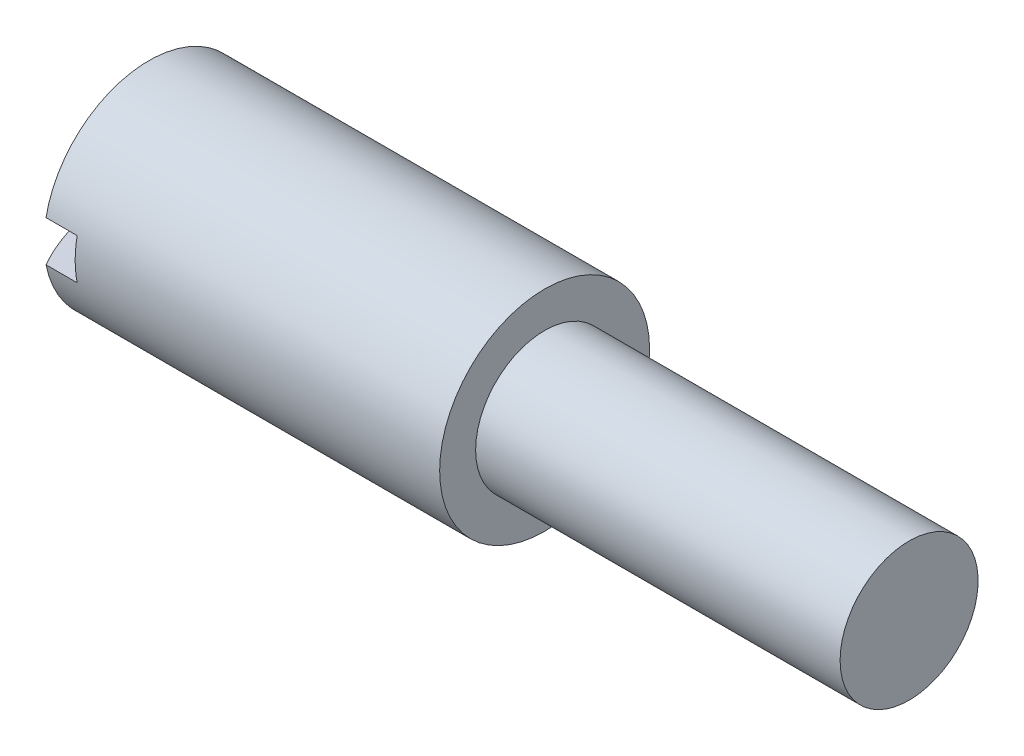
SolidWorks part; units mm, degrees
revolve "BaseBody" add sketch "BodySke" angle 360 about L5
sketch "BodySke" plane through (0, 0, 0) normal (0, 0, 1) x (1, 0, 0)
  line L0 (0.735, -2.7432) -> (47.1574, -2.7432) construction
  line L1 (14.351, 0) -> (14.351, 1.4605)
  line L2 (0.735, 2.7432) -> (13.0683, 2.7432)
  line L3 (14.351, 1.4605) -> (13.0683, 2.7432)
  line L4 (14.351, 0) -> (0, 0)
  line L5 (-12.7, 0) -> (88.9, 0) construction
  line L6 (14.351, 1.4605) -> (14.351, 19.05) construction
  line L7 (14.351, -1.4605) -> (13.0683, -2.7432) construction
  line L8 (1.0592, 12.7) -> (1.0592, -3.175) construction
  arc A1 (0.735, 2.7432) -> (0, 0) centre (5.4864, 0) ccw
  dimension "Crown_radius" = 5.4864
  dimension "Diameter" = 5.4864
  dimension "Nose_ch_ang" = 45
  dimension "Length" = 14.351
  dimension "Flat_dia" = 2.921
  dimension "Advance" = 1.0592
cosmetic thread "ThreadCosmetic" [suppressed] parameters "Thread_minor"=4.2266
extrude "Slot" cut sketch "Sketch2" along normal blind 1.5494
sketch "Sketch2" plane through (0, 0, 0) normal (1, 0, 0) x (0, 0, -1)
  line L1 (2.7432, -0.5334) -> (-2.7432, -0.5334)
  line L2 (2.7432, -0.5334) -> (2.7432, 0.5334)
  line L3 (2.7432, 0.5334) -> (-2.7432, 0.5334)
  line L4 (-2.7432, -0.5334) -> (-2.7432, 0.5334)
  dimension "D1" = 5.4864
  dimension "Slot_width" = 1.0668
  dimension "D3" = 2.7432
  dimension "D2" = 0.5334
material "AISI 1020"
ref_plane "Plane1" through (0, 0, 0) normal (0, 0, 1) x (1, 0, 0)
ref_plane "Plane2" through (0, 0, 0) normal (0, 1, 0) x (1, 0, 0)
ref_plane "Plane3" through (0, 0, 0) normal (1, 0, 0) x (0, 0, -1)
other "Configuration Table"
sketch "ThdSchSke" plane through (0, 0, 0) normal (0, 0, 1) x (1, 0, 0)
  line L0 (0.735, -2.1133) -> (0.294, -2.7432)
  line L1 (0.735, -2.1133) -> (1.1761, -2.7432)
  line L2 (1.1761, -2.7432) -> (1.1761, -3.429)
  line L3 (-3.175, 0) -> (5.1513, 0) construction
  line L4 (0.735, -2.7432) -> (0.735, -0.5334) construction
  line L5 (1.1761, -3.429) -> (0.294, -3.429)
  line L6 (0.294, -3.429) -> (0.294, -2.7432)
  dimension "Diameter" = 5.4864
  dimension "Thread_minor" = 4.2266
revolve "ThreadSchematic" [suppressed] cut sketch "ThdSchSke" angle 360 about L3
pattern_linear "ThdSchPat" [suppressed]
ref_plane "Plano1" through (11.0744, 0, 0) normal (-1, 0, 0) x (0, 0, 1)
sketch "Croquis1" plane through (11.0744, 0, 0) normal (-1, 0, 0) x (0, 0, 1)
  circle A0 centre (0, 0) radius 3.2312
extrude "Cortar-Extruir1" cut sketch "Croquis1" against normal through all
sketch "Croquis4" plane through (11.0744, 0, 0) normal (1, 0, 0) x (0, 0, -1)
  circle A0 centre (0, 0) radius 1.8034
  dimension "D1" = 3.6068
extrude "Saliente-Extruir1" add sketch "Croquis4" along normal blind 9.525
equation "\"D1@Sketch2\" = \"Diameter@BodySke\""
equation "\"D3@Sketch2\" = \"D1@Sketch2\" / 2"
equation "\"D2@Sketch2\" = \"Slot_width@Sketch2\" / 2"
equation "\"Thread_minor@ThdSchSke\" = \"Thread_minor@ThreadCosmetic\""
equation "\"Diameter@ThdSchSke\" = \"Diameter@BodySke\""
equation "\"Overcut@ThdSchSke\" = \"Diameter@BodySke\" * 1.25"
equation "\"Num_threads@ThdSchPat\" = int ( ( \"Length@BodySke\" - ( \"Crown_radius@BodySke\" - sqr ( ( \"Crown_radius@BodySke\" * \"Crown_radius@BodySke\" ) - ( ( \"Diameter@BodySke\" * 0.5 ) * ( \"Diameter@BodySke\" * 0.5 ) ) ) ) - ( ( ( \"Diameter@BodySke\" - \"Flat_dia@BodySke\" ) * 0.5 ) * tan( \"Nose_ch_ang@BodySke\" * 0.017453292 ) ) ) / \"Advance@BodySke\" + 0.999 )  + 1"
equation "\"Advance@ThdSchPat\" = ( \"Length@BodySke\" - ( \"Crown_radius@BodySke\" - sqr ( ( \"Crown_radius@BodySke\" * \"Crown_radius@BodySke\" ) - ( ( \"Diameter@BodySke\" * 0.5 ) * ( \"Diameter@BodySke\" * 0.5 ) ) ) ) - ( ( ( \"Diameter@BodySke\" - \"Flat_dia@BodySke\" ) * 0.5 ) * tan( \"Nose_ch_ang@BodySke\" * 0.017453292 ) ) ) /  (\"Num_threads@ThdSchPat\" - 1) 'relax it"
equation "' \"Num_threads@ThdSchPat\" = \"Num_threads@ThdSchPat\" - sgn( \"Num_threads@ThdSchPat\" - 1) '---chamfered tips only---"
equation "\"A\"= 1 / 32"
equation "\"B\"= 3 / 8"
equation "\"C\"= 3 / 4"
equation "\"D\"= 0.142"
equation "\"E\"= 3 / 64"
equation "\"D1@Croquis4\"=\"D\""
equation "\"D1@Saliente-Extruir1\"=\"B\""
